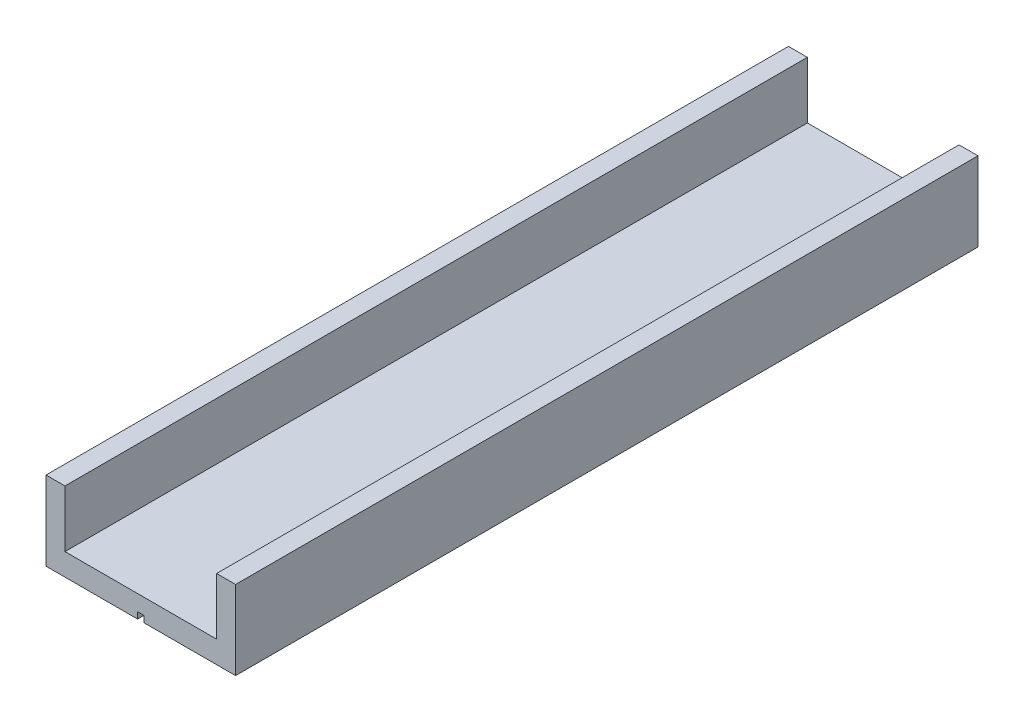
SolidWorks part; units mm, degrees
ref_plane "前视基准面" through (0, 0, 0) normal (0, 0, 1) x (1, 0, 0)
ref_plane "上视基准面" through (0, 0, 0) normal (0, 1, 0) x (1, 0, 0)
ref_plane "右视基准面" through (0, 0, 0) normal (1, 0, 0) x (0, 0, -1)
sketch "草图1" plane through (0, 0, 0) normal (0, 0, 1) x (1, 0, 0)
  line L0 (0, 0) -> (29, 0)
  line L1 (60, 0) -> (31, 0)
  line L2 (0, 0) -> (0, 25)
  line L3 (0, 25) -> (6, 25)
  line L4 (60, 0) -> (60, 25)
  line L5 (29, 0) -> (29, 2)
  line L6 (29, 2) -> (31, 2)
  line L7 (31, 2) -> (31, 0)
  line L8 (6, 25) -> (6, 7)
  line L9 (60, 25) -> (54, 25)
  line L10 (54, 25) -> (54, 7)
  line L11 (54, 7) -> (6, 7)
extrude "凸台-拉伸1" add sketch "草图1" along normal blind 235
